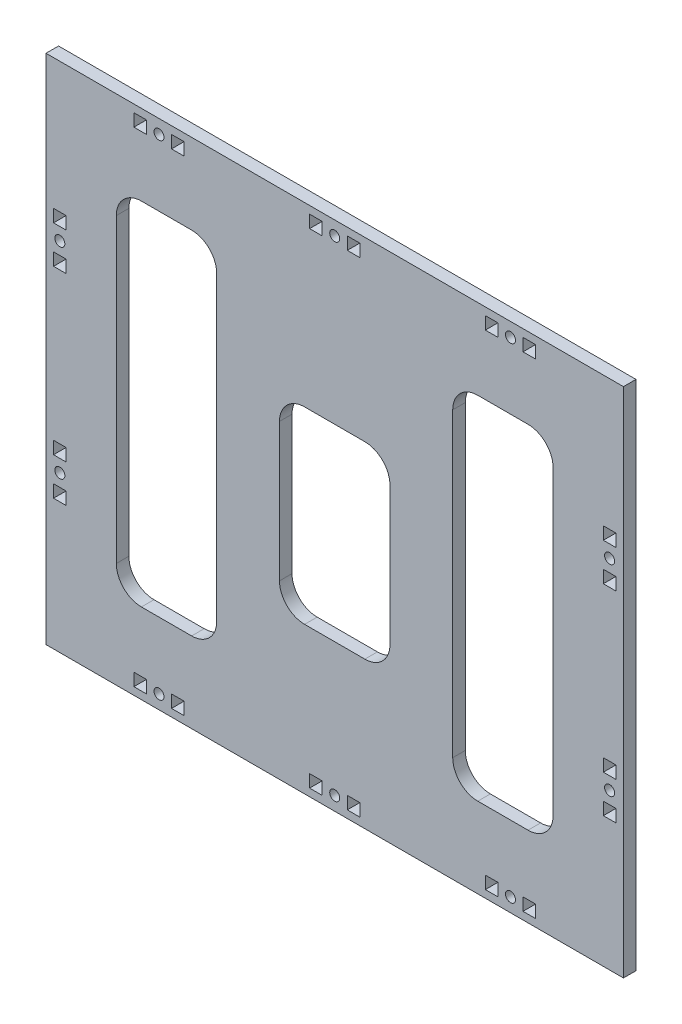
SolidWorks part; units mm, degrees
ref_plane "Plan de face" through (0, 0, 0) normal (0, 0, 1) x (1, 0, 0)
ref_plane "Plan de dessus" through (0, 0, 0) normal (0, 1, 0) x (1, 0, 0)
ref_plane "Plan de droite" through (0, 0, 0) normal (1, 0, 0) x (0, 0, -1)
sketch "Esquisse1" plane through (0, 0, 0) normal (0, 0, 1) x (1, 0, 0)
  line L0 (0, 0) -> (0, 94) construction
  line L1 (-21.3539, 94) -> (23.6911, 94) construction
  line L2 (-182, 188) -> (-182, 196)
  line L3 (-45, 188) -> (-45, 0) construction
  line L4 (-182, 196) -> (48, 196)
  line L5 (48, 196) -> (48, 188)
  line L6 (48, -8) -> (48, 0)
  line L7 (45, 0) -> (45, 188) construction
  line L8 (-182, -8) -> (48, -8)
  line L9 (-182, 0) -> (-182, -8)
  line L10 (-45, 188) -> (-45, 125.5) construction
  line L11 (-45, 125.5) -> (-89, 125.5)
  line L12 (-67, 125.5) -> (-67, 50.5) construction
  line L13 (-67, 50.5) -> (-45, 50.5)
  line L14 (-45, 50.5) -> (-45, 0) construction
  line L15 (-67, 50.5) -> (-89, 50.5)
  line L16 (-89, 50.5) -> (-89, 0) construction
  line L17 (-114, 164) -> (-154, 164)
  line L18 (-20, 164) -> (20, 164)
  line L19 (45, 0) -> (-179, 0) construction
  line L20 (-179, 0) -> (-179, 188) construction
  line L21 (-179, 188) -> (45, 188) construction
  line L22 (-20, 164) -> (-20, 24)
  line L23 (-89, 188) -> (-89, 125.5) construction
  line L24 (-20, 24) -> (20, 24)
  line L25 (-179, 0) -> (-179, 188) construction
  line L26 (-179, 0) -> (-174, 0) construction
  line L27 (-89, 125.5) -> (-89, 50.5)
  line L28 (-45, 50.5) -> (-45, 125.5)
  line L29 (20, 164) -> (20, 24)
  line L30 (-114, 164) -> (-114, 24)
  line L31 (45, 188) -> (48, 188) construction
  line L32 (48, 188) -> (48, 0)
  line L33 (48, 0) -> (45, 0) construction
  line L34 (-182, 0) -> (-179, 0) construction
  line L35 (-179, 188) -> (-182, 188) construction
  line L36 (-182, 188) -> (-182, 0)
  line L37 (-114, 24) -> (-154, 24)
  line L38 (-154, 164) -> (-154, 24)
  line B0 (42.5, 129) -> (42.5, 139) construction
  line B1 (40, 129) -> (40, 124)
  line B2 (40, 129) -> (45, 129)
  line B3 (45, 129) -> (45, 124)
  line B4 (40, 124) -> (45, 124)
  line B5 (40, 139) -> (40, 144)
  line B6 (40, 139) -> (45, 139)
  line B7 (45, 139) -> (45, 144)
  line B8 (40, 144) -> (45, 144)
  line B9 (42.5, 134) -> (35.5276, 134) construction
  circle B10 centre (42.5, 134) radius 2
  line B11 (42.5, 59) -> (42.5, 49) construction
  line B12 (40, 59) -> (40, 64)
  line B13 (40, 59) -> (45, 59)
  line B14 (45, 59) -> (45, 64)
  line B15 (40, 64) -> (45, 64)
  line B16 (40, 49) -> (40, 44)
  line B17 (40, 49) -> (45, 49)
  line B18 (45, 49) -> (45, 44)
  line B19 (40, 44) -> (45, 44)
  line B20 (42.5, 54) -> (35.5276, 54) construction
  circle B21 centre (42.5, 54) radius 2
  line B22 (-176.5, 129) -> (-176.5, 139) construction
  line B23 (-174, 129) -> (-174, 124)
  line B24 (-174, 129) -> (-179, 129)
  line B25 (-179, 129) -> (-179, 124)
  line B26 (-174, 124) -> (-179, 124)
  line B27 (-174, 139) -> (-174, 144)
  line B28 (-174, 139) -> (-179, 139)
  line B29 (-179, 139) -> (-179, 144)
  line B30 (-174, 144) -> (-179, 144)
  line B31 (-176.5, 134) -> (-169.5276, 134) construction
  circle B32 centre (-176.5, 134) radius 2
  line B33 (-176.5, 59) -> (-176.5, 49) construction
  line B34 (-174, 59) -> (-174, 64)
  line B35 (-174, 59) -> (-179, 59)
  line B36 (-179, 59) -> (-179, 64)
  line B37 (-174, 64) -> (-179, 64)
  line B38 (-174, 49) -> (-174, 44)
  line B39 (-174, 49) -> (-179, 49)
  line B40 (-179, 49) -> (-179, 44)
  line B41 (-174, 44) -> (-179, 44)
  line B42 (-176.5, 54) -> (-169.5276, 54) construction
  circle B43 centre (-176.5, 54) radius 2
  line B44 (-132, 190.5) -> (-142, 190.5) construction
  line B45 (-132, 193) -> (-127, 193)
  line B46 (-132, 193) -> (-132, 188)
  line B47 (-132, 188) -> (-127, 188)
  line B48 (-127, 193) -> (-127, 188)
  line B49 (-142, 193) -> (-147, 193)
  line B50 (-142, 193) -> (-142, 188)
  line B51 (-142, 188) -> (-147, 188)
  line B52 (-147, 193) -> (-147, 188)
  line B53 (-137, 190.5) -> (-137, 197.4724) construction
  circle B54 centre (-137, 190.5) radius 2
  line B55 (-2, 190.5) -> (8, 190.5) construction
  line B56 (-2, 193) -> (-7, 193)
  line B57 (-2, 193) -> (-2, 188)
  line B58 (-2, 188) -> (-7, 188)
  line B59 (-7, 193) -> (-7, 188)
  line B60 (8, 193) -> (13, 193)
  line B61 (8, 193) -> (8, 188)
  line B62 (8, 188) -> (13, 188)
  line B63 (13, 193) -> (13, 188)
  line B64 (3, 190.5) -> (3, 197.4724) construction
  circle B65 centre (3, 190.5) radius 2
  line B66 (-2, -2.5) -> (8, -2.5) construction
  line B67 (-2, -5) -> (-7, -5)
  line B68 (-2, -5) -> (-2, 0)
  line B69 (-2, 0) -> (-7, 0)
  line B70 (-7, -5) -> (-7, 0)
  line B71 (8, -5) -> (13, -5)
  line B72 (8, -5) -> (8, 0)
  line B73 (8, 0) -> (13, 0)
  line B74 (13, -5) -> (13, 0)
  line B75 (3, -2.5) -> (3, -9.4724) construction
  circle B76 centre (3, -2.5) radius 2
  line B77 (-132, -2.5) -> (-142, -2.5) construction
  line B78 (-132, -5) -> (-127, -5)
  line B79 (-132, -5) -> (-132, 0)
  line B80 (-132, 0) -> (-127, 0)
  line B81 (-127, -5) -> (-127, 0)
  line B82 (-142, -5) -> (-147, -5)
  line B83 (-142, -5) -> (-142, 0)
  line B84 (-142, 0) -> (-147, 0)
  line B85 (-147, -5) -> (-147, 0)
  line B86 (-137, -2.5) -> (-137, -9.4724) construction
  circle B87 centre (-137, -2.5) radius 2
  line B88 (-72, 190.5) -> (-62, 190.5) construction
  line B89 (-72, 193) -> (-77, 193)
  line B90 (-72, 193) -> (-72, 188)
  line B91 (-72, 188) -> (-77, 188)
  line B92 (-77, 193) -> (-77, 188)
  line B93 (-62, 193) -> (-57, 193)
  line B94 (-62, 193) -> (-62, 188)
  line B95 (-62, 188) -> (-57, 188)
  line B96 (-57, 193) -> (-57, 188)
  line B97 (-67, 190.5) -> (-67, 197.4724) construction
  circle B98 centre (-67, 190.5) radius 2
  line B99 (-72, -190.5) -> (-62, -190.5) construction
  line B100 (-72, -193) -> (-77, -193)
  line B101 (-72, -193) -> (-72, -188)
  line B102 (-72, -188) -> (-77, -188)
  line B103 (-77, -193) -> (-77, -188)
  line B104 (-62, -193) -> (-57, -193)
  line B105 (-62, -193) -> (-62, -188)
  line B106 (-62, -188) -> (-57, -188)
  line B107 (-57, -193) -> (-57, -188)
  line B108 (-67, -190.5) -> (-67, -197.4724) construction
  circle B109 centre (-67, -190.5) radius 2
  line B110 (-72, -2.5) -> (-62, -2.5) construction
  line B111 (-72, -5) -> (-77, -5)
  line B112 (-72, -5) -> (-72, 0)
  line B113 (-72, 0) -> (-77, 0)
  line B114 (-77, -5) -> (-77, 0)
  line B115 (-62, -5) -> (-57, -5)
  line B116 (-62, -5) -> (-62, 0)
  line B117 (-62, 0) -> (-57, 0)
  line B118 (-57, -5) -> (-57, 0)
  line B119 (-67, -2.5) -> (-67, -9.4724) construction
  circle B120 centre (-67, -2.5) radius 2
  dimension "D1" = 3
  dimension "D2" = 140
  dimension "D3" = 40
  dimension "D4" = 188
  dimension "D5" = 75
  dimension "D6" = 140
  dimension "D7" = 224
  dimension "D8" = 80
  dimension "D9" = 3
  dimension "D10" = 140
  dimension "D11" = 204
sketch_block_instance "Trou M4 plots 5mm-1"
sketch_block "Trou M4 plots 5mm" parameters "D2"=4, "D1"=5, "D3"=5, "D4"=10
sketch_block_instance "Trou M4 plots 5mm-3"
sketch_block_instance "Trou M4 plots 5mm-4"
sketch_block_instance "Trou M4 plots 5mm-5"
sketch_block_instance "Trou M4 plots 5mm-6"
sketch_block_instance "Trou M4 plots 5mm-7"
sketch_block_instance "Trou M4 plots 5mm-12"
sketch_block_instance "Trou M4 plots 5mm-13"
sketch_block_instance "Trou M4 plots 5mm-14"
sketch_block_instance "Trou M4 plots 5mm-15"
sketch_block_instance "Trou M4 plots 5mm-16"
extrude "Boss.-Extru.1" add sketch "Esquisse1" along normal blind 5
fillet "Congé1" radius 10 12 edges at (-20, 164, 2.5) (20, 164, 2.5) (20, 24, 2.5) (-20, 24, 2.5) (-45, 50.5, 2.5) (-45, 125.5, 2.5) (-89, 125.5, 2.5) (-89, 50.5, 2.5) (-154, 24, 2.5) (-114, 24, 2.5) (-114, 164, 2.5) (-154, 164, 2.5)
